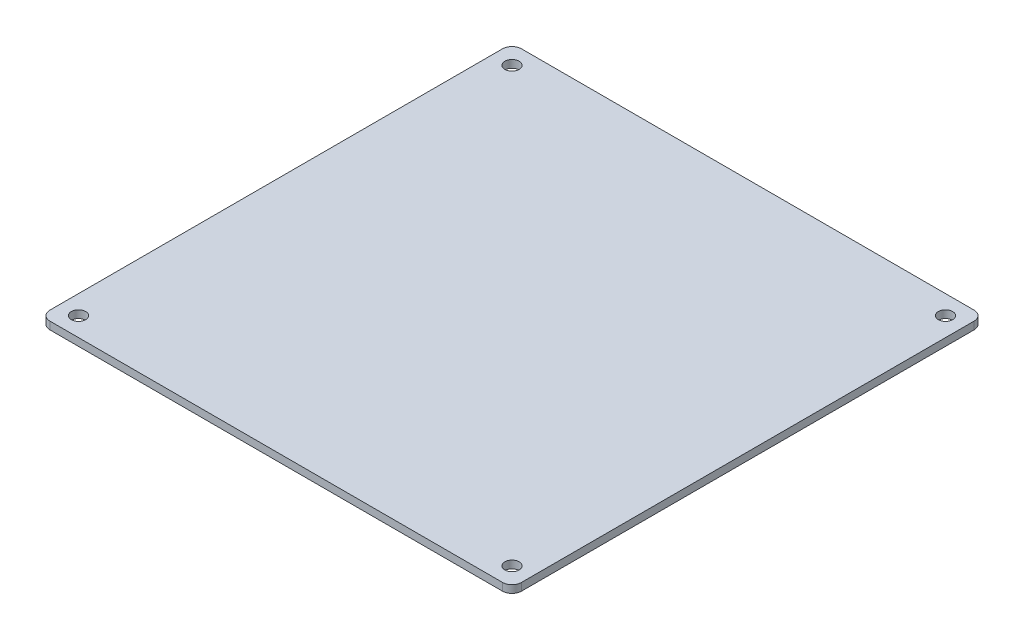
SolidWorks part; units mm, degrees
material "A-玻璃纤维"
ref_plane "前视基准面" through (0, 0, 0) normal (0, 0, 1) x (1, 0, 0)
ref_plane "上视基准面" through (0, 0, 0) normal (0, 1, 0) x (1, 0, 0)
ref_plane "右视基准面" through (0, 0, 0) normal (1, 0, 0) x (0, 0, -1)
other "Configuration Table"
sketch "草图1" plane through (0, 0, 0) normal (0, 1, 0) x (1, 0, 0)
  line L0 (0, 0) -> (73.036, 0) construction
  line L1 (-49.5, -49.5) -> (49.5, -49.5)
  line L2 (-49.5, -49.5) -> (-49.5, 49.5)
  line L3 (-49.5, 49.5) -> (49.5, 49.5)
  line L4 (49.5, -49.5) -> (49.5, 49.5)
  line L5 (-49.5, -49.5) -> (49.5, 49.5) construction
  line L6 (-49.5, 49.5) -> (49.5, -49.5) construction
  line L7 (0, 0) -> (0, 54.0979) construction
  circle A0 centre (-45.5, 45.5) radius 1.5
  circle A1 centre (45.5, 45.5) radius 1.5
  circle A2 centre (45.5, -45.5) radius 1.5
  circle A3 centre (-45.5, -45.5) radius 1.5
  point P0 (0, 0)
  dimension "D3" = 3
  dimension "D1" = 99
  dimension "D2" = 99
  dimension "D4" = 4
extrude "凸台-拉伸1" add sketch "草图1" along normal blind 1.6
fillet "圆角1" radius 2 4 edges at (49.5, 0.8, -49.5) (-49.5, 0.8, -49.5) (49.5, 0.8, 49.5) (-49.5, 0.8, 49.5)
